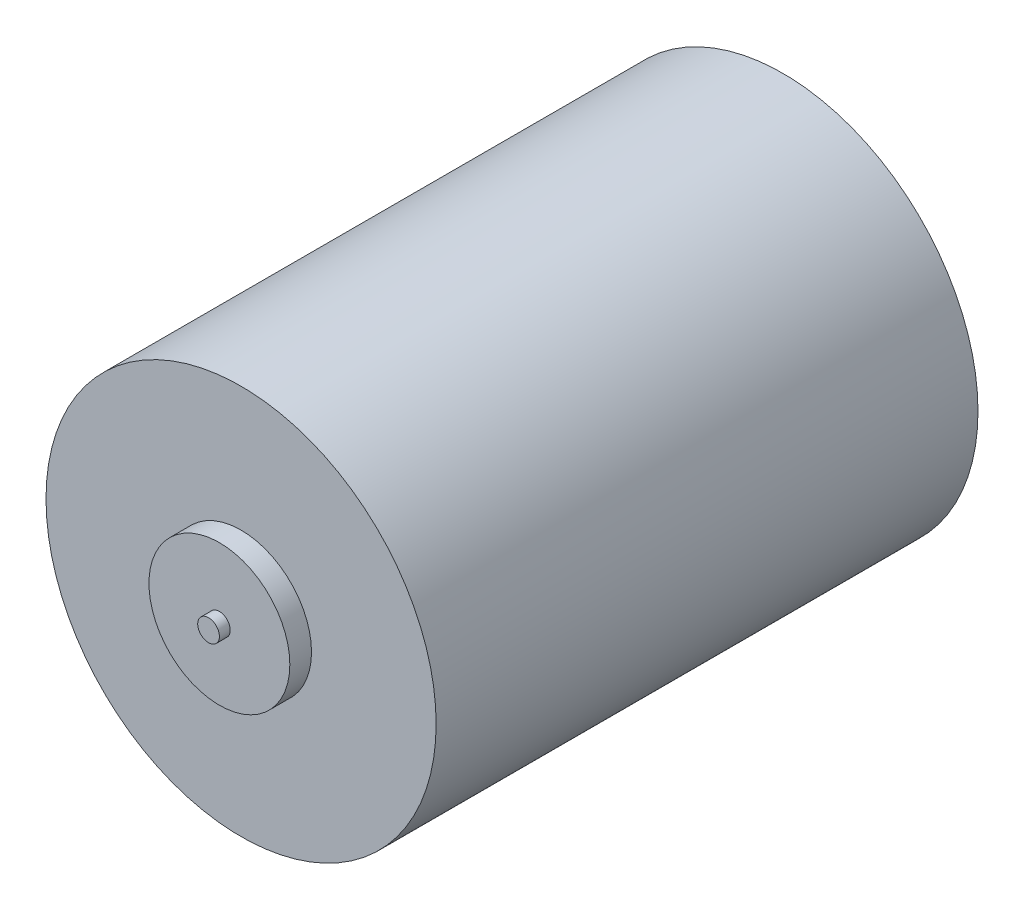
SolidWorks part; units mm, degrees
ref_plane "Front Plane" through (0, 0, 0) normal (0, 0, 1) x (1, 0, 0)
ref_plane "Top Plane" through (0, 0, 0) normal (0, 1, 0) x (1, 0, 0)
ref_plane "Right Plane" through (0, 0, 0) normal (1, 0, 0) x (0, 0, -1)
sketch "Sketch1" plane through (0, 0, 0) normal (0, 0, 1) x (1, 0, 0)
  circle A0 centre (0, 0) radius 18
  dimension "D1" = 36
extrude "Boss-Extrude1" add sketch "Sketch1" along normal blind 50
sketch "Sketch2" plane through (0, 0, 50) normal (0, 0, 1) x (1, 0, 0)
  circle A0 centre (0, 0) radius 6.5
  dimension "D1" = 13
extrude "Boss-Extrude2" add sketch "Sketch2" along normal blind 2
sketch "Sketch3" plane through (0, 0, 52) normal (0, 0, 1) x (1, 0, 0)
  circle A0 centre (0, 0) radius 1
  dimension "D1" = 2
extrude "Boss-Extrude3" add sketch "Sketch3" along normal blind 1
